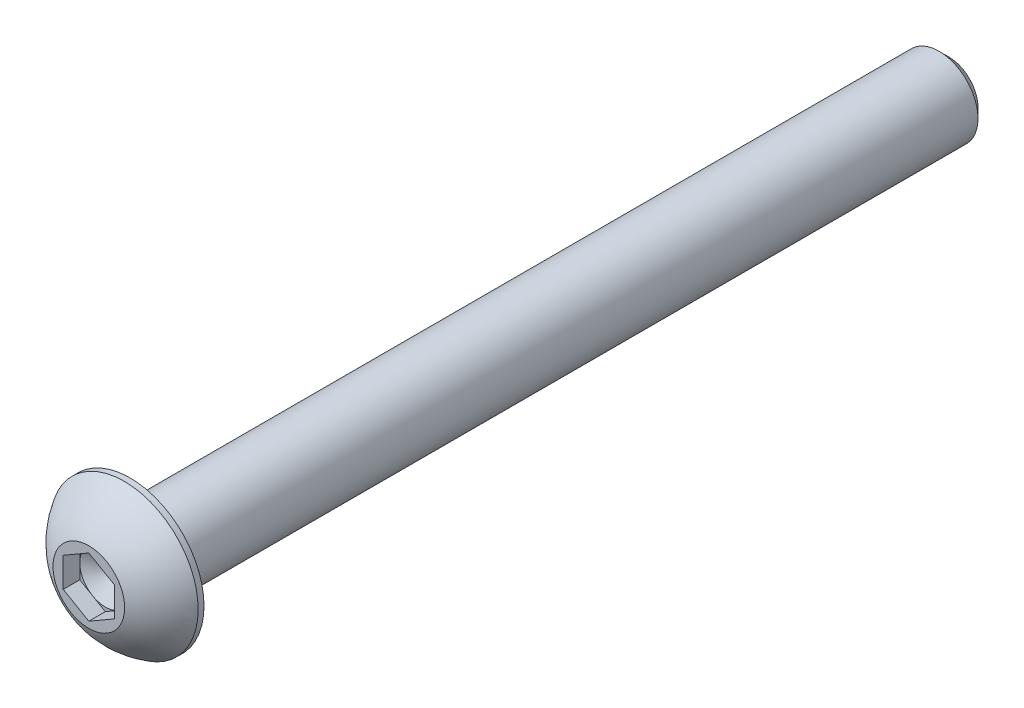
SolidWorks part; units mm, degrees
ref_plane "Front Plane" through (0, 0, 0) normal (0, 0, 1) x (1, 0, 0)
ref_plane "Top Plane" through (0, 0, 0) normal (0, 1, 0) x (1, 0, 0)
ref_plane "Right Plane" through (0, 0, 0) normal (1, 0, 0) x (0, 0, -1)
sketch "Sketch1" plane through (0, 0, 0) normal (1, 0, 0) x (0, 0, -1)
  line L0 (-26.6827, 0) -> (26.6827, 0) construction
  line L1 (-24.1173, 4.5847) -> (-24.1173, -4.5847) construction
  line L2 (-26.6827, 1.5875) -> (-26.6827, -1.5875) construction
  line L3 (26.6827, 2.413) -> (26.6827, -2.413) construction
  line L4 (26.6331, 2.4989) -> (27.03, 1.8115) construction
  line L5 (27.03, 1.8115) -> (27.4268, 2.4989) construction
  line L6 (27.4268, 2.4989) -> (26.6331, 2.4989) construction
  line L7 (27.03, 2.4989) -> (27.03, 2.413) construction
  line L8 (27.03, 1.8115) -> (27.03, 1.8974) construction
  line L9 (26.9804, 1.8974) -> (27.0796, 1.8974)
  line L10 (-26.6827, 2.2225) -> (-26.6827, -2.2225) construction
  line L11 (-24.1173, 4.5847) -> (-24.4802, 4.5847) construction
  line L12 (-26.6827, 1.5875) -> (-25.6565, 1.5875) construction
  line L13 (-25.6565, 1.5875) -> (-24.74, 0) construction
  point P5 (-24.1173, 0)
  point P10 (23.9046, -2.413)
  dimension "Drive Size" = 3.175
  dimension "Head Diameter" = 9.1694
  dimension "Head Height" = 2.5654
  dimension "Diameter" = 4.826
  dimension "Thread Length" = 50.8
  dimension "D1" = 2.7781
  dimension "Pitch" = 0.7937
  dimension "D2" = 0.0992
  dimension "D3" = 4.445
  dimension "D4" = 0.3629
  dimension "D5" = 60
  dimension "D6" = 1.0262
sketch "Sketch2" plane through (0, 0, 0) normal (1, 0, 0) x (0, 0, -1)
  line L0 (-26.6827, 1.5875) -> (-26.6827, 2.2225)
  line L1 (-24.4802, 4.5847) -> (-24.1173, 4.5847)
  line L2 (-24.1173, 4.5847) -> (-24.1173, 2.413)
  line L3 (-24.1173, 4.5847) -> (-24.1173, -4.5847) construction
  line L4 (-24.1173, 2.413) -> (26.0874, 2.413)
  line L5 (26.6827, 1.8177) -> (26.6827, 0)
  line L6 (-26.6827, 1.5875) -> (-25.6565, 1.5875)
  line L7 (-25.6565, 1.5875) -> (-24.74, 0)
  line L8 (26.6827, 0) -> (-24.74, 0)
  line L9 (26.0874, 2.413) -> (26.6827, 1.8177)
  arc A0 (-24.4802, 4.5847) -> (-26.6827, 2.2225) centre (-21.9311, 0) ccw
  point P13 (26.6827, 2.413)
  dimension "D1" = 0.5953
  dimension "D2" = 45
revolve "Revolve1" add sketch "Sketch2" angle 360 about L0
sketch "Sketch3" plane through (0, 0, 0) normal (0, 0, 1) x (1, 0, 0)
  line L1 (0, 1.8331) -> (-1.5875, 0.9165)
  line L2 (-1.5875, 0.9165) -> (-1.5875, -0.9165)
  line L3 (-1.5875, -0.9165) -> (0, -1.8331)
  line L4 (0, -1.8331) -> (1.5875, -0.9165)
  line L5 (1.5875, -0.9165) -> (1.5875, 0.9165)
  line L6 (1.5875, 0.9165) -> (0, 1.8331)
  circle A0 centre (0, 0) radius 1.5875 construction
extrude "Cut-Extrude1" cut sketch "Sketch3" along normal through all from vertex at 25.6565 starting at point (0, 1.5875, 25.6565)
equation "\"D2@Sketch1\"=\"Pitch@Sketch1\"*.125"
equation "\"D1@Sketch1\"=\"Pitch@Sketch1\"*3.5"
equation "\"D3@Sketch1\"=\"Drive Size@Sketch1\"*1.4"
equation "\"D4@Sketch1\"=(\"D3@Sketch1\"-\"Drive Size@Sketch1\")/3.5"
equation "\"D6@Sketch1\"=\"Head Height@Sketch1\"*.40"
equation "\"D1@Sketch2\"=\"Pitch@Sketch1\"*.750"
